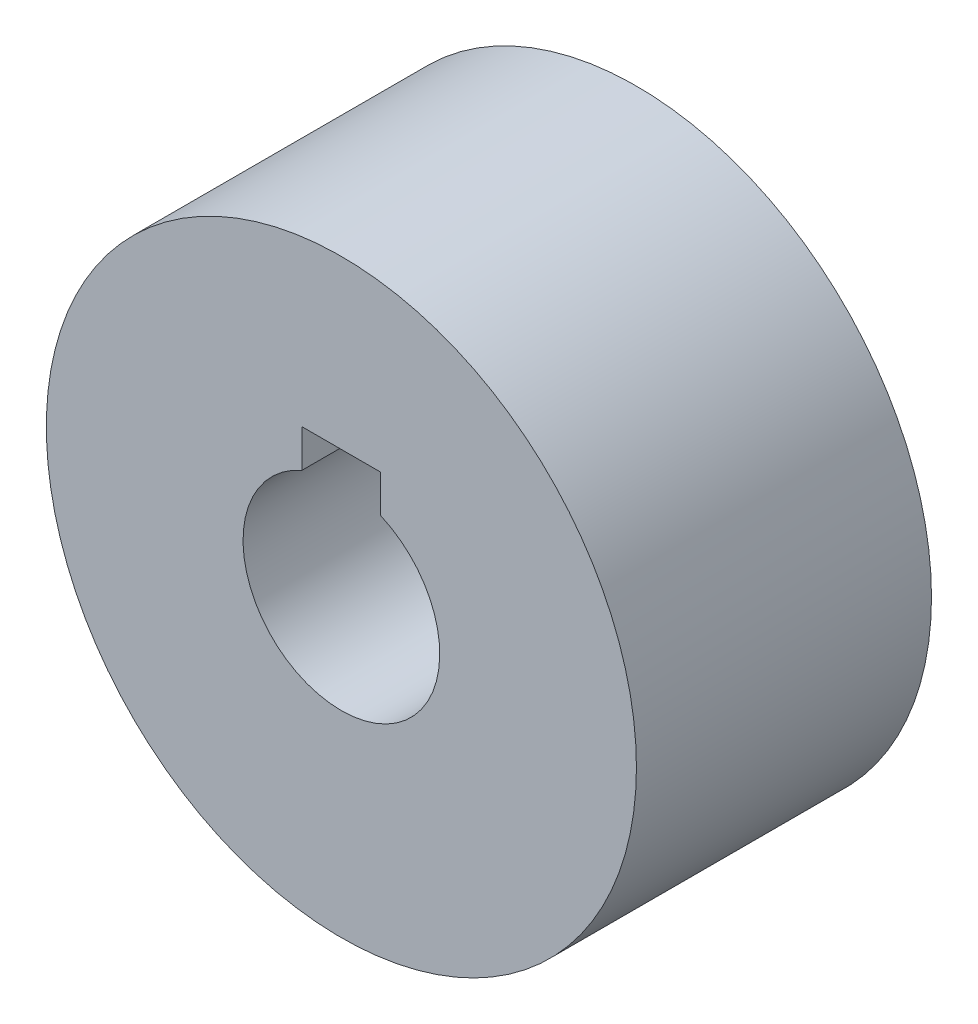
SolidWorks part; units mm, degrees
ref_plane "Front Plane" through (0, 0, 0) normal (0, 0, 1) x (1, 0, 0)
ref_plane "Top Plane" through (0, 0, 0) normal (0, 1, 0) x (1, 0, 0)
ref_plane "Right Plane" through (0, 0, 0) normal (1, 0, 0) x (0, 0, -1)
sketch "Sketch1" plane through (0, 0, 0) normal (0, 0, 1) x (1, 0, 0)
  line L0 (4, 9.1652) -> (4, 13)
  line L1 (4, 13) -> (-4, 13)
  line L2 (-4, 13) -> (-4, 9.1652)
  circle A0 centre (0, 0) radius 30
  arc A1 (-4, 9.1652) -> (4, 9.1652) centre (0, 0) ccw
  point P8 (0, 13)
  dimension "D1" = 60
  dimension "D2" = 20
  dimension "D3" = 8
  dimension "D4" = 23
extrude "Boss-Extrude1" add sketch "Sketch1" along normal blind 30
